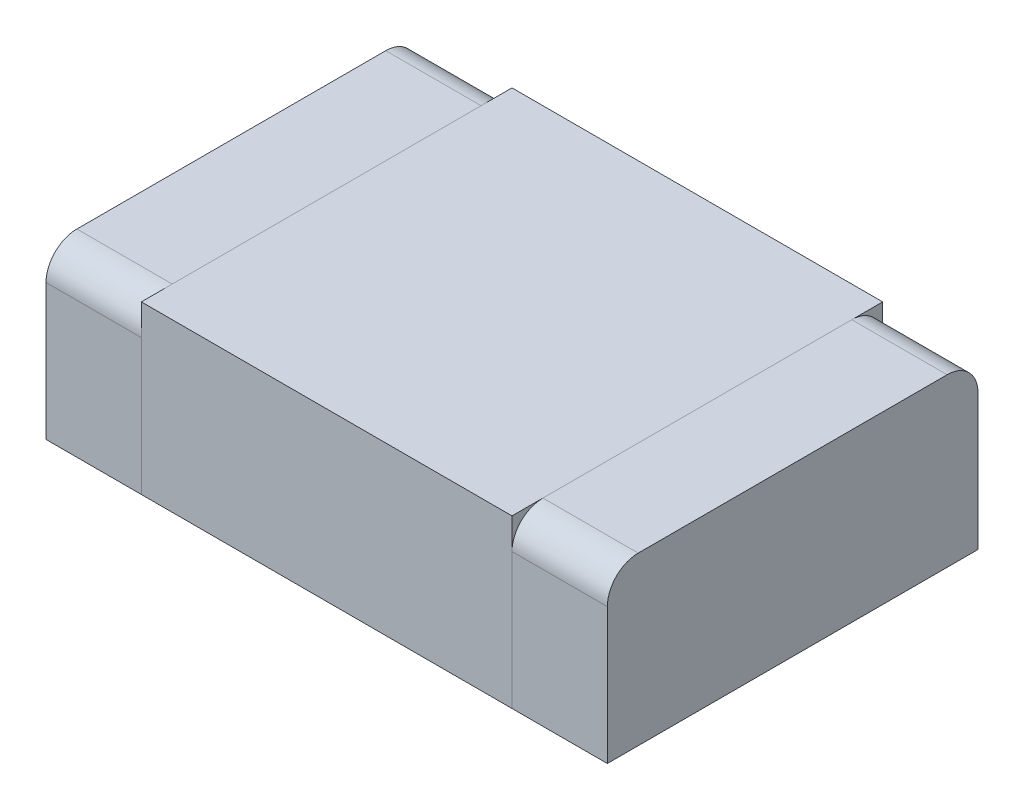
SolidWorks part; units mm, degrees
ref_plane "Front Plane" through (0, 0, 0) normal (0, 0, 1) x (1, 0, 0)
ref_plane "Top Plane" through (0, 0, 0) normal (0, 1, 0) x (1, 0, 0)
ref_plane "Right Plane" through (0, 0, 0) normal (1, 0, 0) x (0, 0, -1)
sketch "Sketch1" plane through (0, 0, 0) normal (0, 1, 0) x (1, 0, 0)
  line L1 (0.6, 0.6) -> (-0.6, 0.6)
  line L2 (0.6, 0.6) -> (0.6, -0.6)
  line L3 (0.6, -0.6) -> (-0.6, -0.6)
  line L4 (-0.6, 0.6) -> (-0.6, -0.6)
  line L5 (0.6, 0.6) -> (-0.6, -0.6) construction
  line L6 (0.6, -0.6) -> (-0.6, 0.6) construction
  point P0 (0, 0)
  dimension "D1" = 1.2
extrude "Boss-Extrude1" add sketch "Sketch1" along normal blind 0.54
sketch "Sketch2" plane through (0, 0, 0) normal (0, 1, 0) x (1, 0, 0)
  line L0 (-0.6, 0.6) -> (-0.9086, 0.6)
  line L1 (-0.9086, 0.6) -> (-0.9086, -0.6)
  line L2 (-0.9086, -0.6) -> (-0.6, -0.6)
  line L10 (0.6, 0.6) -> (0.9086, 0.6)
  line L11 (0.9086, 0.6) -> (0.9086, -0.6)
  line L12 (0.9086, -0.6) -> (0.6, -0.6)
  line L24 (0.6, 0.6) -> (0.6, 0.0616)
  line L25 (0.6, -0.6) -> (0.6, 0.6) construction
  line L26 (0.6, 0.0616) -> (0.5478, 0.0616)
  line L27 (0.5478, 0.0616) -> (0.5478, 0.4436)
  line L28 (0.5478, 0.4436) -> (-0.2846, 0.4436)
  line L29 (-0.2846, 0.4436) -> (-0.2846, 0.2892)
  line L30 (-0.2846, 0.2892) -> (0.0517, 0.2892)
  line L31 (0.0517, 0.2892) -> (0.0517, -0.3959)
  line L32 (0.0517, -0.3959) -> (0.5478, -0.3959)
  line L33 (0.5478, -0.3959) -> (0.5478, -0.0616)
  line L34 (0.5478, -0.0616) -> (0.6, -0.0616)
  line L35 (0.6, -0.0616) -> (0.6, -0.6)
  line L36 (-0.6, 0.6) -> (-0.6, 0.0616)
  line L37 (-0.6, 0.6) -> (-0.6, -0.6) construction
  line L38 (-0.6, 0.0616) -> (-0.4119, 0.0616)
  line L39 (-0.4119, 0.0616) -> (-0.4119, 0.2338)
  line L40 (-0.4119, 0.2338) -> (0.0082, 0.2338)
  line L41 (0.0082, 0.2338) -> (0.0082, -0.3774)
  line L42 (0.0082, -0.3774) -> (-0.4119, -0.3774)
  line L43 (-0.4119, -0.3774) -> (-0.4119, -0.0616)
  line L44 (-0.4119, -0.0616) -> (-0.6, -0.0616)
  line L45 (-0.6, -0.0616) -> (-0.6, -0.6)
extrude "Boss-Extrude2" add sketch "Sketch2" along normal blind 0.54 separate body
sketch "Sketch3" plane through (0, 0, 0) normal (0, 0, 1) x (1, 0, 0)
  line L0 (0.0082, 0.54) -> (0.0082, 0) construction
  line L1 (0.6, 0) -> (-0.6, 0)
  line L2 (0.6, 0) -> (0.6, 0.2029)
  line L3 (0.6, 0.54) -> (-0.6, 0.54)
  line L4 (-0.6, 0) -> (-0.6, 0.2029)
  line L5 (0.6, 0) -> (-0.6, 0.54) construction
  line L6 (0.6, 0.54) -> (-0.6, 0) construction
  line L7 (-0.6, 0.4865) -> (0.6, 0.4865)
  line L8 (-0.6, 0.2029) -> (0.6, 0.2029)
  line L9 (-0.6, 0.4865) -> (-0.6, 0.54)
  line L10 (0.6, 0.4865) -> (0.6, 0.54)
  point P0 (0, 0.27)
  point P10 (0.0082, 0.27)
extrude "Cut-Extrude1" cut sketch "Sketch3" against normal through all both and the other way through all
fillet "Fillet1" radius 0.1 2 edges at (-0.7543, 0.54, 0.6) (-0.7543, 0.54, -0.6)
fillet "Fillet2" radius 0.1 2 edges at (0.7543, 0.54, 0.6) (0.7543, 0.54, -0.6)
sketch "Sketch4" [suppressed] plane through (0, 0.54, 0) normal (0, 1, 0) x (1, 0, 0)
  circle A0 centre (0.4286, 0) radius 0.0557
extrude "Boss-Extrude4" [suppressed] add sketch "Sketch4" along normal blind 0.01 separate body
